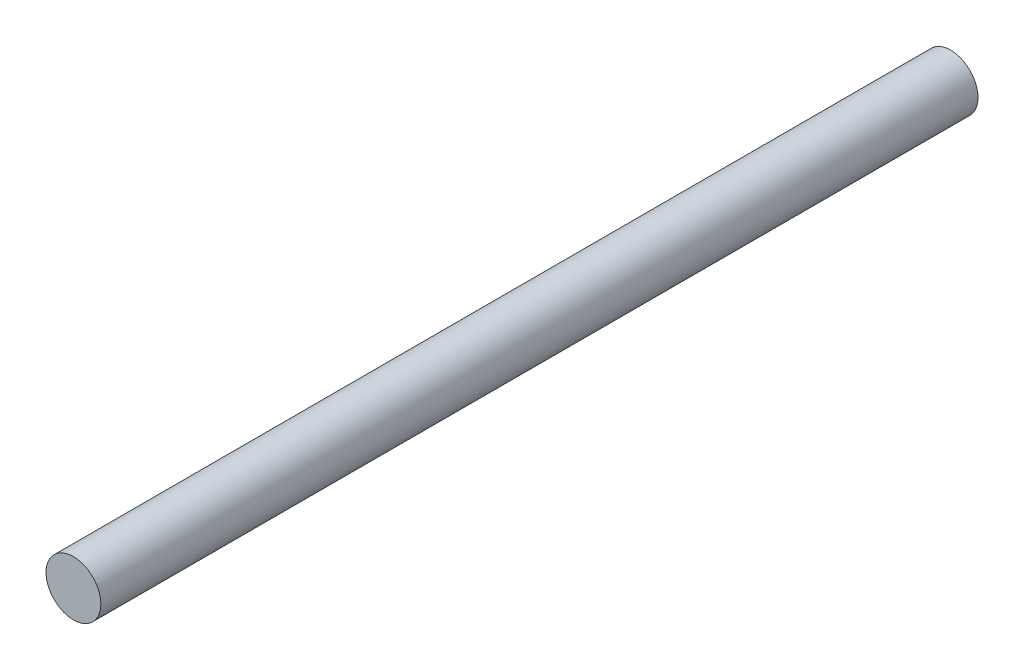
SolidWorks part; units mm, degrees
ref_plane "Front Plane" through (0, 0, 0) normal (0, 0, 1) x (1, 0, 0)
ref_plane "Top Plane" through (0, 0, 0) normal (0, 1, 0) x (1, 0, 0)
ref_plane "Right Plane" through (0, 0, 0) normal (1, 0, 0) x (0, 0, -1)
sketch "Sketch1" plane through (0, 0, 0) normal (0, 0, 1) x (1, 0, 0)
  circle A0 centre (0, 0) radius 2.5
  dimension "D1" = 5
extrude "Boss-Extrude1" add sketch "Sketch1" along normal blind 60
sketch "Sketch3" plane through (0, 0, 0) normal (0, 0, -1) x (-1, 0, 0)
  circle A0 centre (0, 0) radius 2.5
extrude "Boss-Extrude2" add sketch "Sketch3" along normal blind 20
